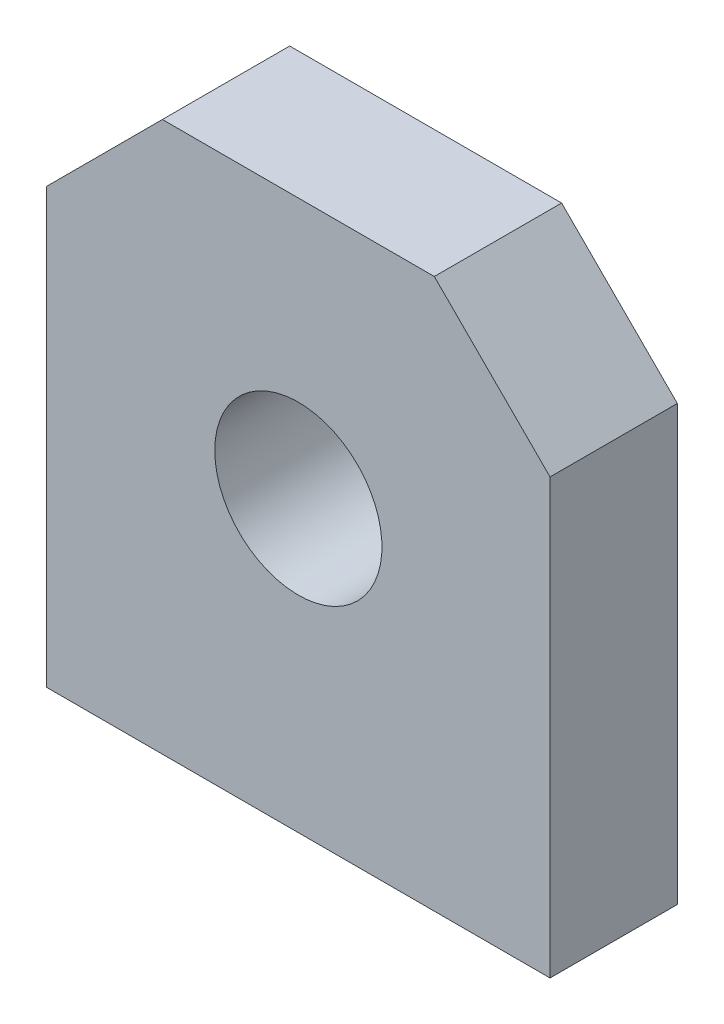
SolidWorks part; units mm, degrees
material "ABS PC"
ref_plane "Front Plane" through (0, 0, 0) normal (0, 0, 1) x (1, 0, 0)
ref_plane "Top Plane" through (0, 0, 0) normal (0, 1, 0) x (1, 0, 0)
ref_plane "Right Plane" through (0, 0, 0) normal (1, 0, 0) x (0, 0, -1)
sketch "Sketch1" plane through (0, 0, 0) normal (0, 0, 1) x (1, 0, 0)
  line L0 (-5.5245, 3.4925) -> (-2.9845, 6.0325)
  line L1 (-5.5245, -6.0325) -> (5.5245, -6.0325)
  line L2 (-5.5245, -6.0325) -> (-5.5245, 3.4925)
  line L3 (-2.9845, 6.0325) -> (2.9845, 6.0325)
  line L4 (5.5245, -6.0325) -> (5.5245, 3.4925)
  line L5 (-5.5245, -6.0325) -> (5.5245, 6.0325) construction
  line L6 (-5.5245, 6.0325) -> (5.5245, -6.0325) construction
  line L7 (5.5245, 3.4925) -> (2.9845, 6.0325)
  point P0 (0, 0)
  dimension "D1" = 11.049
  dimension "D2" = 12.065
extrude "Boss-Extrude1" add sketch "Sketch1" along normal blind 2.794
sketch "Sketch2" plane through (0, 0, 0) normal (0, 0, -1) x (-1, 0, 0)
  line L0 (5.5245, -6.0325) -> (-5.5245, -6.0325) construction
  circle A0 centre (0, 0.3175) radius 1.8349
  dimension "D1" = 6.35
extrude "Cut-Extrude1" cut sketch "Sketch2" against normal blind 2.794
